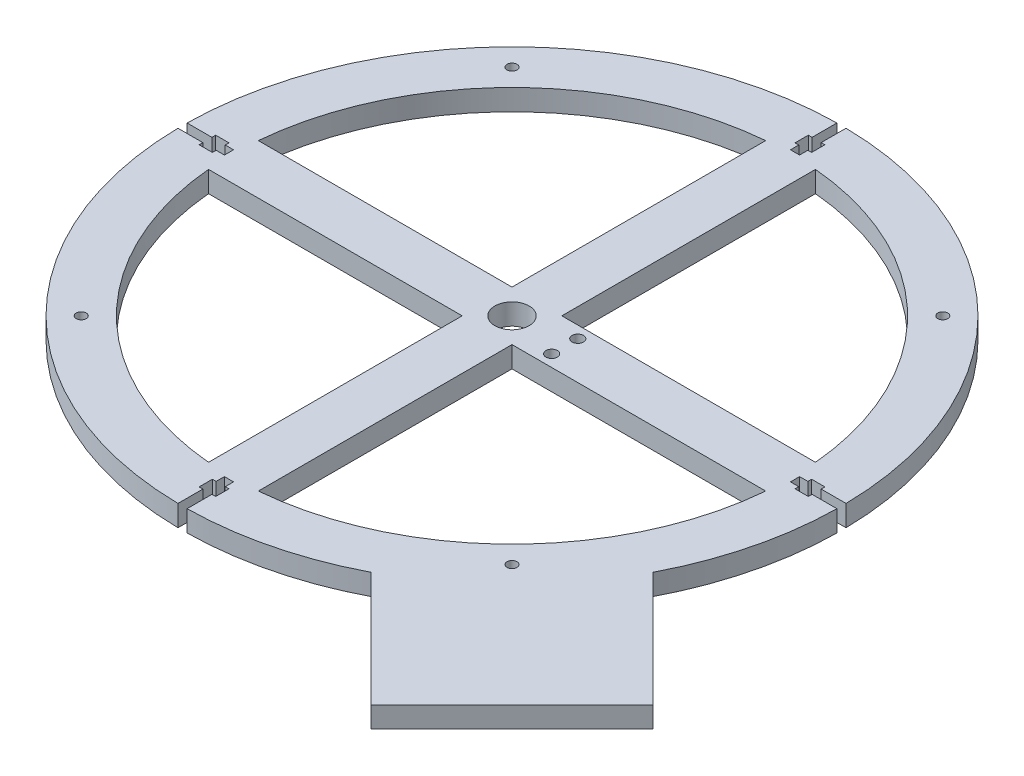
SolidWorks part; units mm, degrees
material "6061 Alloy"
ref_plane "Front Plane" through (0, 0, 0) normal (0, 0, 1) x (1, 0, 0)
ref_plane "Top Plane" through (0, 0, 0) normal (0, 1, 0) x (1, 0, 0)
ref_plane "Right Plane" through (0, 0, 0) normal (1, 0, 0) x (0, 0, -1)
sketch "Sketch1" plane through (0, 0, 0) normal (0, 1, 0) x (1, 0, 0)
  line L0 (0, -99.238) -> (0, 99.238) construction
  line L1 (-99.238, 0) -> (99.238, 0) construction
  line L2 (-98.9542, -7.5) -> (98.9542, -7.5)
  line L3 (7.5, -98.9542) -> (7.5, 98.9542)
  line L4 (-98.9542, 7.5) -> (98.9542, 7.5)
  line L5 (-7.5, -98.9542) -> (-7.5, 98.9542)
  line L6 (-7.5, -99.238) -> (-7.5, 99.238) construction
  line L7 (7.5, -99.238) -> (7.5, 99.238) construction
  line L8 (-99.238, -7.5) -> (99.238, -7.5) construction
  line L9 (-99.238, 7.5) -> (99.238, 7.5) construction
  line L11 (80.2566, -122.683) -> (122.683, -80.2566)
  line L16 (101.4698, -101.4698) -> (70.1719, -70.1719) construction
  line L17 (122.683, -80.2566) -> (88.1018, -45.6754)
  line L23 (80.2566, -122.683) -> (45.6754, -88.1018)
  line L33 (122.683, -80.2566) -> (91.3851, -48.9587) construction
  line L34 (80.2566, -122.683) -> (48.9587, -91.3851) construction
  circle A0 centre (0, 0) radius 100 construction
  circle A1 centre (0, 0) radius 99.238
  circle A2 centre (0, 0) radius 84.238
  point P7 (0, 0)
  point P11 (0, 0)
  dimension "D1" = 200
  dimension "D2" = 0.762
  dimension "D3" = 15
  dimension "D6" = 45
  dimension "D8" = 43.5
  dimension "D4" = 7.5
  dimension "D5" = 7.5
  dimension "D11" = 30
  dimension "D12" = 30
extrude "Boss-Extrude1" add sketch "Sketch1" along normal mid plane 6.35
sketch "Sketch2" plane through (0, 0, 0) normal (0, 1, 0) x (1, 0, 0)
  line L0 (-1.375, 85.238) -> (-1.375, 99.238)
  line L1 (-1.375, 85.238) -> (1.375, 85.238)
  line L2 (-1.375, 99.238) -> (1.375, 99.238)
  line L3 (1.375, 85.238) -> (1.375, 99.238)
  line L4 (-1.375, 85.238) -> (1.375, 99.238) construction
  line L5 (-1.375, 99.238) -> (1.375, 85.238) construction
  line L6 (-2.5, 87.738) -> (-2.5, 91.738)
  line L7 (-2.5, 87.738) -> (2.5, 87.738)
  line L8 (-2.5, 91.738) -> (2.5, 91.738)
  line L9 (2.5, 87.738) -> (2.5, 91.738)
  line L10 (-2.5, 87.738) -> (2.5, 91.738) construction
  line L11 (-2.5, 91.738) -> (2.5, 87.738) construction
  line L12 (0, -1000) -> (0, 49000) construction
  line L13 (-1000, 0) -> (49000, 0) construction
  circle A0 centre (0, 0) radius 99.238 construction
  point P1 (0, 92.238)
  point P2 (0, 89.738)
  dimension "D1" = 2.75
  dimension "D2" = 14
  dimension "D3" = 4
  dimension "D4" = 5
  dimension "D5" = 2.5
extrude "Cut-Extrude1" cut sketch "Sketch2" against normal through all both and the other way through all contours L7 L0 L1 L3 | L8 L0 L7 L3 | L7 L9 L8 L3 | L0 L8 L3 L2 | L8 L6 L7 L0
pattern_circular "CirPattern1" count 4 over 360 about axis through (0, 0, 0) along (0, 1, 0) of "Cut-Extrude1"
hole_wizard "Ø3.0 (3) Diameter Hole1" positions "Sketch3" profile "Sketch4" hole size "Ø3.0" standard "ANSI Metric" end condition up to next
sketch "Sketch3" plane through (0, 3.175, 0) normal (0, 1, 0) x (1, 0, 0)
  line L0 (-70.1719, -70.1719) -> (70.1719, 70.1719) construction
  line L2 (-70.1719, 70.1719) -> (70.1719, -70.1719) construction
  line L4 (70.1719, 70.1719) -> (59.5653, 59.5653)
  line L6 (70.1719, -70.1719) -> (59.5653, -59.5653)
  line L8 (-70.1719, -70.1719) -> (-59.5653, -59.5653)
  line L10 (-70.1719, 70.1719) -> (-59.5653, 59.5653)
  arc A2 (83.9035, 7.5) -> (7.5, 83.9035) centre (0, 0) ccw construction
  arc A3 (7.5, -83.9035) -> (83.9035, -7.5) centre (0, 0) ccw construction
  arc A4 (-83.9035, -7.5) -> (-7.5, -83.9035) centre (0, 0) ccw construction
  arc A5 (-7.5, 83.9035) -> (-83.9035, 7.5) centre (0, 0) ccw construction
  circle A6 centre (0, 0) radius 99.238
  arc A7 (-1.375, 99.2285) -> (-99.2285, 1.375) centre (0, 0) ccw construction
  point P107 (0, 0)
  point P324 (0, 0)
  point P360 (-64.8686, 64.8686)
  point P362 (64.8686, 64.8686)
  point P364 (64.8686, -64.8686)
  point P366 (-64.8686, -64.8686)
sketch "Sketch4" plane through (-64.8686, 3.175, 64.8686) normal (1, 0, 0) x (0, 0, 1)
  line L0 (0, 0) -> (0, 6.35)
  line L1 (0, 6.35) -> (1.5, 6.35)
  line L2 (1.5, 6.35) -> (1.5, 0)
  line L5 (1.5, 0) -> (0, 0)
  line L11 (0, -6.35) -> (0, 107.95) construction
  dimension "Thru Hole Dia." = 3
  dimension "Thru Hole Depth" = 6.35
hole_wizard "3/8 Clearance Hole1" positions "Sketch5" profile "Sketch6" hole size "3/8" standard "ANSI Inch" end condition up to next
sketch "Sketch5" plane through (0, 3.175, 0) normal (0, 1, 0) x (1, 0, 0)
  point P0 (0, 0)
sketch "Sketch6" plane through (0, 3.175, 0) normal (1, 0, 0) x (0, 0, 1)
  line L0 (0, 0) -> (0, 6.35)
  line L1 (0, 6.35) -> (5.1587, 6.35)
  line L2 (5.1587, 6.35) -> (5.1587, 0)
  line L5 (5.1587, 0) -> (0, 0)
  line L11 (0, -6.35) -> (0, 107.95) construction
  dimension "Thru Hole Dia." = 10.3175
  dimension "Thru Hole Depth" = 6.35
hole_wizard "#8-32 Tapped Hole1" [suppressed] positions "Sketch7" profile "Sketch8" tap size "#8-32" standard "ANSI Inch"
sketch "Sketch7" plane through (101.4698, 0, 101.4698) normal (0.7071, 0, 0.7071) x (0.7071, 0, -0.7071)
  line L0 (30, 3.175) -> (30, -3.175) construction
  line L1 (-30, 3.175) -> (-30, -3.175) construction
  point P0 (-20, 0)
  point P2 (20, 0)
  dimension "D1" = 10
  dimension "D2" = 10
sketch "Sketch8" plane through (87.3277, 0, 115.612) normal (0, 1, 0) x (0.7071, 0, -0.7071)
  line L0 (0, 0) -> (0, 11.7478)
  line L1 (0, 11.7478) -> (1.7272, 10.71)
  line L2 (1.7272, 10.71) -> (1.7272, 0)
  line L5 (1.7272, 0) -> (0, 0)
  line L10 (0, 11.7478) -> (-1.7272, 10.71) construction
  line L11 (0, -6.35) -> (0, 107.95) construction
  dimension "Tap Drill Dia." = 3.4544
  dimension "Tap Drill Depth" = 10.71
  dimension "Drill Angle" = 118
cosmetic thread "Hole Thread1" [suppressed] parameters "D1"=8.33, "D2"=4.1656
cosmetic thread "Hole Thread2" [suppressed] parameters "D1"=8.33, "D2"=4.1656
hole_wizard "3/16 (0.1875) Dowel Hole1" [suppressed] positions "Sketch9" profile "Sketch10" hole size "3/16" standard "ANSI Inch"
sketch "Sketch9" plane through (101.4698, 0, 101.4698) normal (0.7071, 0, 0.7071) x (0.7071, 0, -0.7071)
  line L0 (30, 3.175) -> (30, -3.175) construction
  line L1 (-30, 3.175) -> (-30, -3.175) construction
  point P0 (-10, 0)
  point P2 (10, 0)
  dimension "D1" = 20
  dimension "D2" = 20
sketch "Sketch10" plane through (94.3988, 0, 108.5409) normal (0, 1, 0) x (0.7071, 0, -0.7071)
  line L0 (0, 0) -> (0, 14.2608)
  line L1 (0, 14.2608) -> (2.3812, 12.83)
  line L2 (2.3812, 12.83) -> (2.3812, 0)
  line L5 (2.3812, 0) -> (0, 0)
  line L10 (0, 14.2608) -> (-2.3813, 12.83) construction
  line L11 (0, -6.35) -> (0, 107.95) construction
  dimension "Hole Dia." = 4.7625
  dimension "Hole Depth" = 12.83
  dimension "Drill Angle" = 118
hole_wizard "#4 Clearance Hole1" positions "Sketch11" profile "Sketch12" hole size "#4" standard "ANSI Inch" end condition up to next
sketch "Sketch11" plane through (0, 3.175, 0) normal (0, 1, 0) x (1, 0, 0)
  point P0 (15.88, -3.94)
  point P2 (15.88, 3.94)
  point P5 (0, 0)
  point P10 (17.904, -11.5379)
  point P13 (0, 0)
  dimension "D1" = 3.94
  dimension "D2" = 15.88
  dimension "D3" = 3.94
sketch "Sketch12" plane through (15.88, 3.175, 3.94) normal (1, 0, 0) x (0, 0, 1)
  line L0 (0, 0) -> (0, 6.35)
  line L1 (0, 6.35) -> (1.7272, 6.35)
  line L2 (1.7272, 6.35) -> (1.7272, 0)
  line L5 (1.7272, 0) -> (0, 0)
  line L11 (0, -6.35) -> (0, 107.95) construction
  dimension "Thru Hole Dia." = 3.4544
  dimension "Thru Hole Depth" = 6.35
